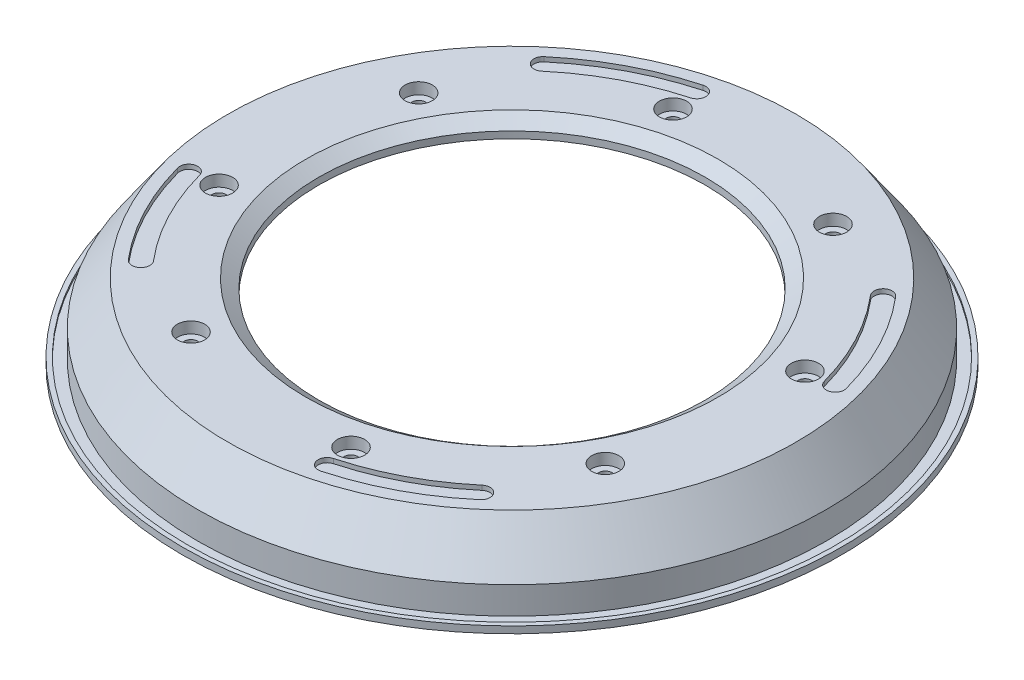
SolidWorks part; units mm, degrees
material "PF"
ref_plane "前视基准面" through (0, 0, 0) normal (0, 0, 1) x (1, 0, 0)
ref_plane "上视基准面" through (0, 0, 0) normal (0, 1, 0) x (1, 0, 0)
ref_plane "右视基准面" through (0, 0, 0) normal (1, 0, 0) x (0, 0, -1)
sketch "草图1" plane through (0, 0, 0) normal (0, 1, 0) x (1, 0, 0)
  circle A0 centre (0, 0) radius 72.5
  circle A1 centre (0, 0) radius 65
  dimension "D1" = 145
  dimension "D2" = 130
extrude "凸台-拉伸1" add sketch "草图1" along normal blind 1
sketch "草图2" plane through (0, 0, 0) normal (0, 0, 1) x (1, 0, 0)
  line L0 (-72.5, 1) -> (-72.5, 1.5)
  line L1 (-72.5, 1.5) -> (-71.5, 1.5)
  line L2 (-71.5, 1.5) -> (-71.5, 1)
  line L3 (72.5, 1) -> (-72.5, 1) construction
  line L4 (-71.5, 1) -> (-72.5, 1)
  line L5 (0, 15.8078) -> (0, -11.2895) construction
  dimension "D1" = 1
  dimension "D2" = 0.5
revolve "旋转1" add sketch "草图2" angle 360 about L5
sketch "草图3" plane through (0, 1, 0) normal (0, 1, 0) x (1, 0, 0)
  circle A0 centre (0, 0) radius 67.1733
extrude "切除-拉伸1" cut sketch "草图3" against normal blind 500
sketch "草图4" plane through (0, 1, 0) normal (0, 1, 0) x (1, 0, 0)
  circle A0 centre (0, 0) radius 67.1733
  circle A1 centre (0, 0) radius 69.1733
  circle A2 centre (0, 0) radius 67.1733 construction
  dimension "D1" = 2
extrude "凸台-拉伸2" add sketch "草图4" along normal blind 6
sketch "草图5" plane through (0, 0, 0) normal (0, 0, 1) x (1, 0, 0)
  line L0 (0, 1.5) -> (0, 16.5) construction
  line L1 (72.5, 1.5) -> (-72.5, 1.5) construction
  line L2 (-69.1733, 7) -> (-62.5, 16.5)
  line L3 (-62.5, 16.5) -> (-45.358, 16.5)
  line L5 (-42.5, 14.5) -> (-61.4608, 14.5)
  line L6 (-61.4608, 14.5) -> (-66.7291, 7)
  line L7 (69.1733, 7) -> (-69.1733, 7) construction
  line L8 (-66.7291, 7) -> (-69.1733, 7)
  line L9 (-42.5, 14.5) -> (-45.358, 16.5)
  dimension "D1" = 15
  dimension "D2" = 2
  dimension "D3" = 2
  dimension "D4" = 62.5
  dimension "D5" = 15
  dimension "D6" = 42.5
revolve "旋转3" add sketch "草图5" angle 360 about L0
sketch "草图9" plane through (0, 16.5, 0) normal (0, 1, 0) x (1, 0, 0)
  circle A0 centre (25.0436, 45.5721) radius 3
extrude "切除-拉伸3" cut sketch "草图9" against normal blind 50
pattern_circular "阵列(圆周)1" count 8 over 360 about axis through (0, 0, 0) along (0, 1, 0) of "切除-拉伸3"
ref_plane "基准面1" through (0, 13, 0) normal (0, -1, 0) x (-1, 0, 0)
sketch "草图10" plane through (0, 13, 0) normal (0, -1, 0) x (1, 0, 0)
  circle A0 centre (0, 0) radius 42.5
  circle A1 centre (0, 0) radius 64.0839
ref_plane "基准面2" through (0, 13, 0) normal (0, -1, 0) x (-1, 0, 0)
extrude "凸台-拉伸4" add sketch "草图10" against normal up to surface (1.5 mm away) up to face at (-14.5158, 14.5, -46.9329)
sketch "草图11" plane through (0, 16.5, 0) normal (0, 1, 0) x (1, 0, 0)
  circle A0 centre (14.5158, -49.9329) radius 3
extrude "切除-拉伸4" cut sketch "草图11" against normal blind 50
pattern_circular "阵列(圆周)2" count 8 over 360 about axis through (0, 0, 0) along (0, 1, 0) of "切除-拉伸4"
sketch "草图12" plane through (0, 0, 0) normal (0, 0, 1) x (1, 0, 0)
  line L0 (-69.1733, 7) -> (-62.5, 16.5)
  line L1 (-62.5, 16.5) -> (-70.7522, 16.5)
  line L2 (-70.7522, 16.5) -> (-69.1733, 7)
  line L3 (0, 0) -> (0, 29.4807) construction
revolve "切除-旋转1" cut sketch "草图12" angle 360 about L3
sketch "草图13" plane through (0, 13, 0) normal (0, -1, 0) x (1, 0, 0)
  circle A0 centre (49.9329, -14.5158) radius 3
  circle A1 centre (49.9329, -14.5158) radius 1.5
  dimension "D1" = 3
  dimension "D2" = 6
extrude "凸台-拉伸5" add sketch "草图13" against normal blind 1
pattern_circular "阵列(圆周)3" count 8 over 360 about axis through (0, 0, 0) along (0, 1, 0) of "凸台-拉伸5"
sketch "草图14" plane through (0, 16.5, 0) normal (0, 1, 0) x (1, 0, 0)
  arc A0 (-15.7414, 57.7909) -> (-38.69, 45.7237) centre (0, 0) ccw
  arc A1 (-14.7071, 53.9938) -> (-36.1479, 42.7195) centre (0, 0) ccw
  arc A2 (-38.69, 45.7237) -> (-36.1479, 42.7195) centre (-37.419, 44.2216) ccw
  arc A3 (-14.7071, 53.9938) -> (-15.7414, 57.7909) centre (-15.2243, 55.8923) ccw
  point P4 (14.5158, -49.9329)
  point P7 (-25.0436, -45.5721)
extrude "切除-拉伸5" cut sketch "草图14" against normal blind 1
pattern_circular "阵列(圆周)4" count 4 over 360 about axis through (0, 0, 0) along (0, 1, 0) of "切除-拉伸5"
